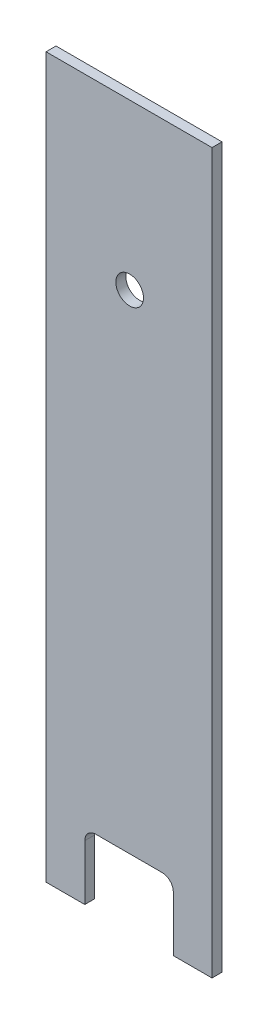
SolidWorks part; units mm, degrees
ref_plane "Plano frontal" through (0, 0, 0) normal (0, 0, 1) x (1, 0, 0)
ref_plane "Plano superior" through (0, 0, 0) normal (0, 1, 0) x (1, 0, 0)
ref_plane "Plano direito" through (0, 0, 0) normal (1, 0, 0) x (0, 0, -1)
sketch "Esboço1" plane through (0, 0, 0) normal (0, 0, 1) x (1, 0, 0)
  line L1 (-26.6322, 23.6195) -> (3.3678, 23.6195)
  line L2 (-26.6322, 23.6195) -> (-26.6322, -106.3805)
  line L3 (-26.6322, -106.3805) -> (3.3678, -106.3805)
  line L4 (3.3678, 23.6195) -> (3.3678, -106.3805)
  dimension "D1" = 130
extrude "Ressalto-extrusão1" add sketch "Esboço1" along normal blind 1.8
sketch "Esboço2" plane through (0, 0, 0) normal (0, 0, -1) x (-1, 0, 0)
  line L0 (10.5088, -4.5637) -> (12.5265, -7.6891) construction
  circle A0 centre (11.5177, -6.1264) radius 2.5
  dimension "D1" = 5
extrude "Corte-extrusão1" cut sketch "Esboço2" against normal blind 10
sketch "Esboço3" plane through (0, 0, 0) normal (0, 0, -1) x (-1, 0, 0)
  line L1 (26.6322, -106.3805) -> (-3.3678, -106.3805) construction
  line L5 (3.6322, -106.3805) -> (19.6322, -106.3805)
  line L6 (19.6322, -106.3805) -> (19.6322, -96.3805)
  line L7 (17.6322, -94.3805) -> (5.6322, -94.3805)
  line L8 (3.6322, -96.3805) -> (3.6322, -106.3805)
  arc A0 (17.6322, -94.3805) -> (19.6322, -96.3805) centre (17.6322, -96.3805) cw
  arc A1 (5.6322, -94.3805) -> (3.6322, -96.3805) centre (5.6322, -96.3805) ccw
  point P5 (11.6322, -106.3805)
  point P10 (11.6322, -106.3805)
  dimension "D1" = 2
extrude "Corte-extrusão2" cut sketch "Esboço3" against normal blind 10.2
